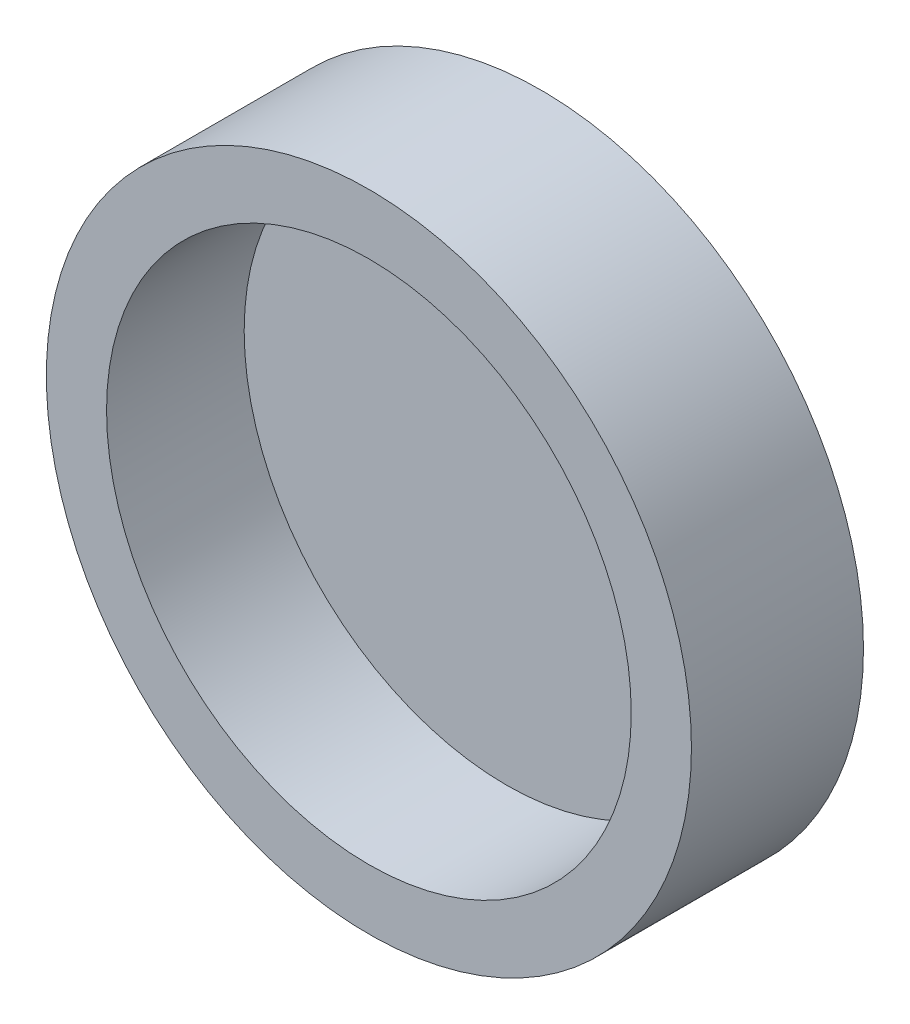
SolidWorks part; units mm, degrees
ref_plane "Front Plane" through (0, 0, 0) normal (1, 0, 0) x (0, 1, 0)
ref_plane "Top Plane" through (0, 0, 0) normal (0, 0, 1) x (0, 1, 0)
ref_plane "Right Plane" through (0, 0, 0) normal (0, 1, 0) x (-1, 0, 0)
sketch "Sketch1" plane through (0, 0, 0) normal (0, 0, 1) x (0, 1, 0)
  circle A0 centre (0, 0) radius 7.5
  dimension "D1" = 15
extrude "Boss-Extrude1" add sketch "Sketch1" along normal blind 4 contours A0
sketch "Sketch2" plane through (0, 0, 4) normal (0, 0, 1) x (1, 0, 0)
  circle A0 centre (0, 0) radius 6.1
  dimension "D1" = 12.2
extrude "Cut-Extrude1" cut sketch "Sketch2" against normal blind 3.2
